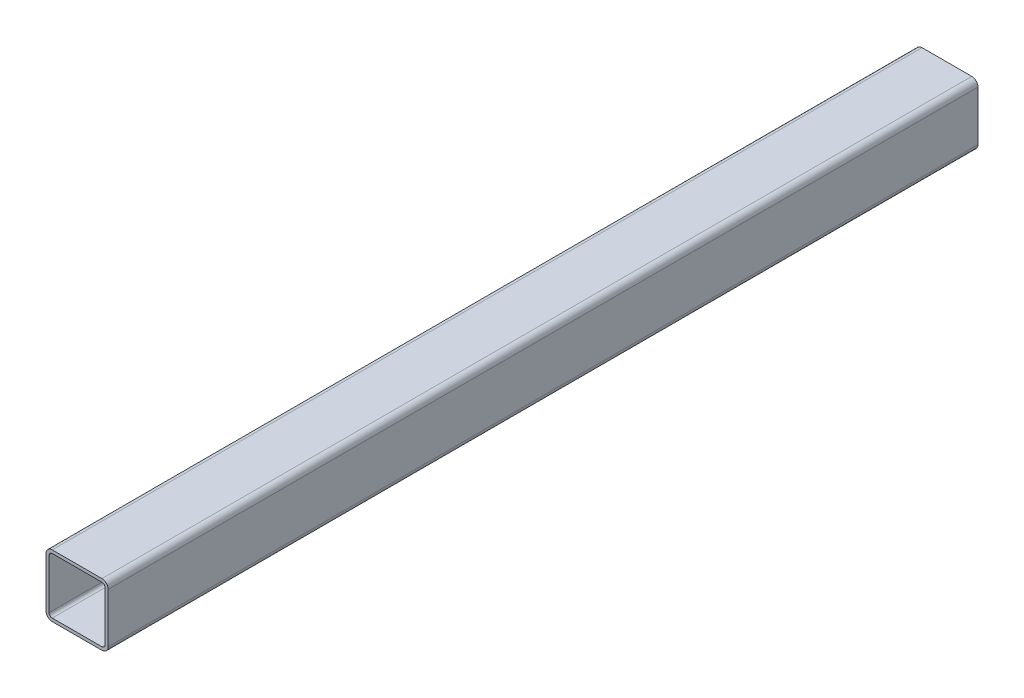
SolidWorks part; units mm, degrees
material "1.4305 (X8CrNiS18-9)"
ref_plane "Ön Düzlem" through (0, 0, 0) normal (0, 0, 1) x (1, 0, 0)
ref_plane "Üst Düzlem" through (0, 0, 0) normal (0, 1, 0) x (1, 0, 0)
ref_plane "Sağ Düzlem" through (0, 0, 0) normal (1, 0, 0) x (0, 0, -1)
sketch "Çizim1" plane through (0, 0, 0) normal (0, 0, 1) x (1, 0, 0)
  line L0 (-18, 16) -> (-18, -16)
  line L1 (-16, 20) -> (16, 20)
  line L2 (-20, 16) -> (-20, -16)
  line L3 (-16, -20) -> (16, -20)
  line L4 (20, 16) -> (20, -16)
  line L5 (-20, 20) -> (20, -20) construction
  line L6 (-20, -20) -> (20, 20) construction
  line L7 (-16, -18) -> (16, -18)
  line L8 (18, 16) -> (18, -16)
  line L9 (-16, 18) -> (16, 18)
  arc A0 (20, -16) -> (16, -20) centre (16, -16) cw
  arc A1 (16, 20) -> (20, 16) centre (16, 16) cw
  arc A2 (-16, 20) -> (-20, 16) centre (-16, 16) ccw
  arc A3 (-20, -16) -> (-16, -20) centre (-16, -16) ccw
  arc A4 (-18, -16) -> (-16, -18) centre (-16, -16) ccw
  arc A5 (18, -16) -> (16, -18) centre (16, -16) cw
  arc A6 (16, 18) -> (18, 16) centre (16, 16) cw
  arc A7 (-16, 18) -> (-18, 16) centre (-16, 16) ccw
  point P0 (0, 0)
  dimension "D3" = 4
  dimension "D1" = 40
  dimension "D2" = 40
  dimension "D4" = 2
extrude "Yükseklik-Ekstrüzyon1" add sketch "Çizim1" along normal blind 560
sketch "Çizim2" plane through (0, 0, 0) normal (0, 0, -1) x (-1, 0, 0)
  line L0 (-18.8284, 18.8284) -> (18.8284, -18.8284) construction
  arc A0 (-16, 20) -> (-20, 16) centre (-16, 16) ccw construction
  arc A1 (16, -20) -> (20, -16) centre (16, -16) ccw construction
ref_plane "Düzlem1" through (0, 0, 0) normal (0.7071, -0.7071, 0) x (-0.7071, -0.7071, 0)
